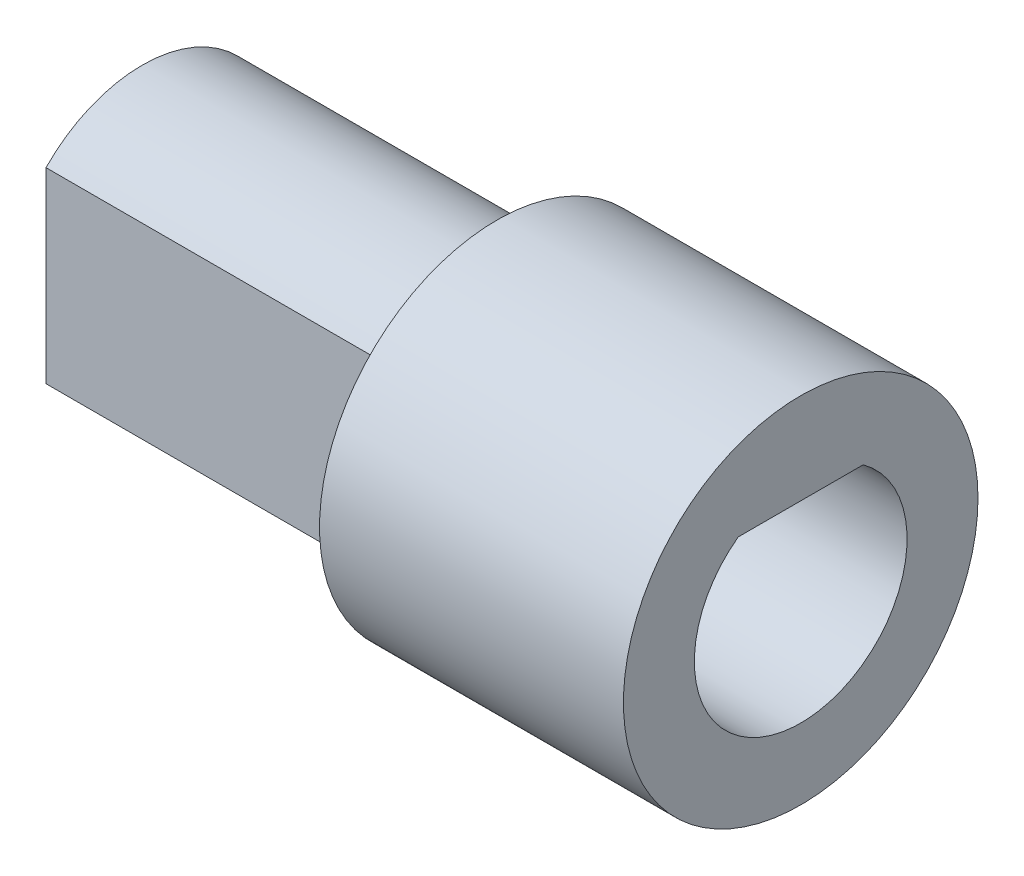
SolidWorks part; units mm, degrees
ref_plane "Front Plane" through (0, 0, 0) normal (0, 0, 1) x (1, 0, 0)
ref_plane "Top Plane" through (0, 0, 0) normal (0, 1, 0) x (1, 0, 0)
ref_plane "Right Plane" through (0, 0, 0) normal (1, 0, 0) x (0, 0, -1)
sketch "Sketch1" plane through (0, 0, 0) normal (1, 0, 0) x (0, 0, -1)
  line L0 (-1.9, 1.8473) -> (-1.9, -1.8473)
  line L1 (1.9, 1.8473) -> (1.9, -1.8473)
  arc A0 (-1.9, -1.8473) -> (1.9, -1.8473) centre (0, 0) ccw
  arc A2 (1.9, 1.8473) -> (-1.9, 1.8473) centre (0, 0) ccw
  point P1 (0, 0)
  dimension "D3" = 5.3
  dimension "D1" = 3.8
  dimension "D2" = 1.9
sketch "Sketch5" plane through (0, 0, 0) normal (1, 0, 0) x (0, 0, -1)
  line L0 (-1.2329, 1.7) -> (1.2329, 1.7) construction
  arc A0 (-1.2329, 1.7) -> (1.2329, 1.7) centre (0, 0) ccw construction
  circle A1 centre (0, 0) radius 3.5
  dimension "D1" = 4.2
  dimension "D3" = 7
  dimension "D2" = 1.7
extrude "Boss-Extrude1" add sketch "Sketch1" against normal blind 7
extrude "Boss-Extrude2" add sketch "Sketch5" along normal blind 6 contours A1
fillet "Fillet1" radius 0.5 4 edges at (0, 0, -1.9) (0, -2.65, 0) (0, 0, 1.9) (0, 2.65, 0)
sketch "Sketch7" plane through (6, 0, 0) normal (1, 0, 0) x (0, 0, -1)
  line L0 (-1.2329, 1.7) -> (1.2329, 1.7)
  arc A0 (-1.2329, 1.7) -> (1.2329, 1.7) centre (0, 0) ccw
  arc A1 (-1.2329, 1.7) -> (1.2329, 1.7) centre (0, 0) ccw construction
extrude "Cut-Extrude1" cut sketch "Sketch7" against normal blind 5
equation "\"D2@Sketch1\"=\"D1@Sketch1\"/2"
